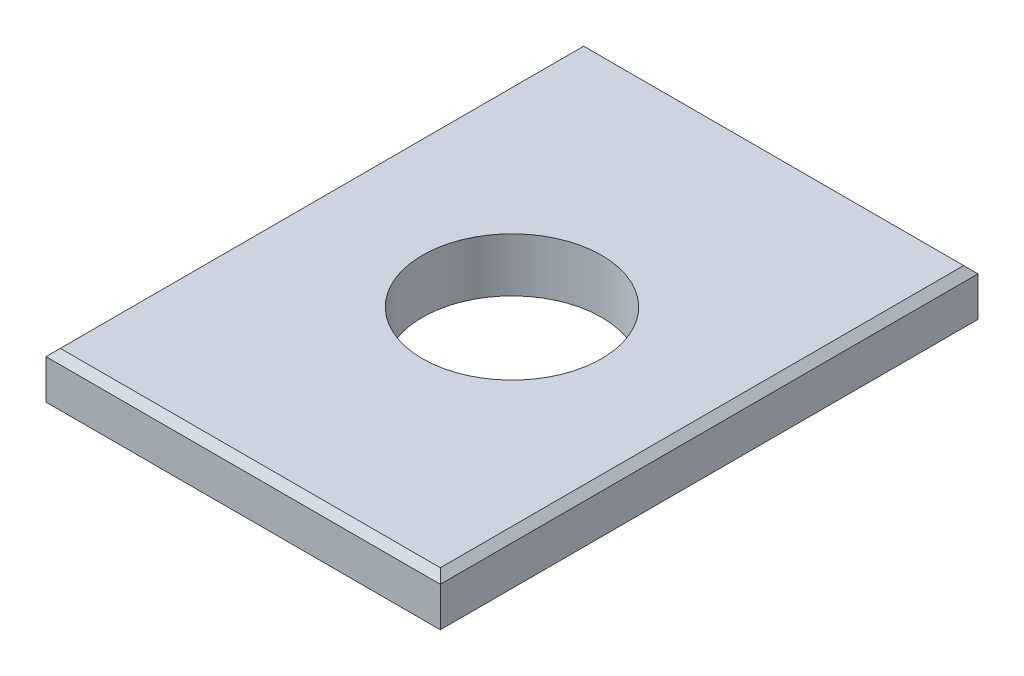
SolidWorks part; units mm, degrees
ref_plane "正面" through (0, 0, 0) normal (0, 0, 1) x (1, 0, 0)
ref_plane "平面" through (0, 0, 0) normal (0, 1, 0) x (1, 0, 0)
ref_plane "右側面" through (0, 0, 0) normal (1, 0, 0) x (0, 0, -1)
sketch "ｽｹｯﾁ1" plane through (0, 0, 0) normal (0, 1, 0) x (1, 0, 0)
  line L1 (-5.5, 7.5) -> (5.5, 7.5)
  line L2 (-5.5, 7.5) -> (-5.5, -7.5)
  line L3 (-5.5, -7.5) -> (5.5, -7.5)
  line L4 (5.5, 7.5) -> (5.5, -7.5)
  line L5 (-5.5, 7.5) -> (5.5, -7.5) construction
  line L6 (-5.5, -7.5) -> (5.5, 7.5) construction
  point P0 (0, 0)
  dimension "D1" = 11
  dimension "D2" = 15
extrude "ﾎﾞｽ - 押し出し1" add sketch "ｽｹｯﾁ1" along normal blind 1.5
sketch "ｽｹｯﾁ2" plane through (0, 1.5, 0) normal (0, 1, 0) x (1, 0, 0)
  circle A0 centre (0, 0) radius 2.5
  dimension "D1" = 5
extrude "ｶｯﾄ - 押し出し1" cut sketch "ｽｹｯﾁ2" against normal blind 1.5
chamfer "面取り1" distance 0.2 angle 45 4 edges at (0, 1.5, -7.5) (5.5, 1.5, 0) (0, 1.5, 7.5) (-5.5, 1.5, 0)
chamfer "面取り2" distance 0.2 angle 45 4 edges at (0, 0, 7.5) (5.5, 0, 0) (0, 0, -7.5) (-5.5, 0, 0)
